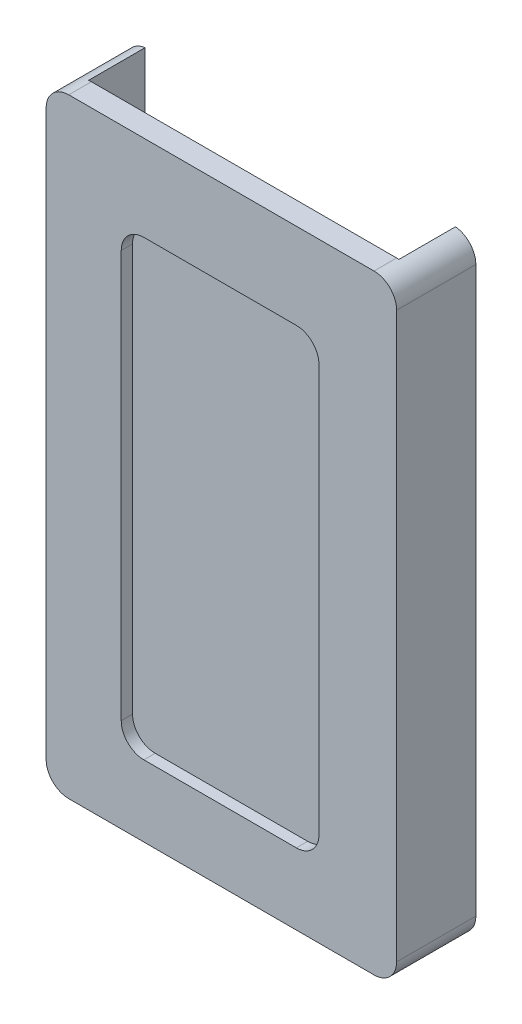
SolidWorks part; units mm, degrees
ref_plane "Front Plane" through (0, 0, 0) normal (0, 0, 1) x (1, 0, 0)
ref_plane "Top Plane" through (0, 0, 0) normal (0, 1, 0) x (1, 0, 0)
ref_plane "Right Plane" through (0, 0, 0) normal (1, 0, 0) x (0, 0, -1)
sketch "草图5" plane through (0, 0, 17) normal (0, 0, 1) x (1, 0, 0)
  line L0 (67.6414, -26.8877) -> (67.6414, -76.7564) construction
  line L1 (36.6667, -24.8877) -> (67.6414, -24.8877)
  line L2 (36.6667, -24.8877) -> (36.6667, -78.7564)
  line L3 (36.6667, -78.7564) -> (67.6414, -78.7564)
  line L4 (67.6414, -24.8877) -> (67.6414, -78.7564)
  line L5 (38.4139, -24.9037) -> (38.4139, -28.6161) construction
  line L6 (38.4139, -26.7599) -> (65.7955, -26.7599)
  line L7 (38.4139, -26.7599) -> (38.4139, -77.1753)
  line L8 (38.4139, -77.1753) -> (65.7955, -77.1753)
  line L9 (65.7955, -26.7599) -> (65.7955, -77.1753)
  point P14 (0, 0)
extrude "凸台-拉伸3" add sketch "草图5" along normal blind 5 contours L2 L1 L4 L3 | L7 L6 L9 L8
sketch "草图6" plane through (0, -24.8877, 0) normal (0, 1, 0) x (1, 0, 0)
  line L1 (38.4139, -17) -> (65.8413, -17)
  line L2 (38.4139, -17) -> (38.4139, -22)
  line L3 (38.4139, -22) -> (65.8413, -22)
  line L4 (65.8413, -17) -> (65.8413, -22)
  point P4 (0, 0)
extrude "切除-拉伸4" cut sketch "草图6" against normal blind 4
sketch "草图8" plane through (0, 0, 17) normal (0, 0, -1) x (-1, 0, 0)
  line L0 (-38.4139, -77.1753) -> (-65.7955, -77.1753) construction
  line L1 (-55.1901, -77.1753) -> (-49.0701, -77.1753)
  line L2 (-55.1901, -77.1753) -> (-55.1901, -78.7564)
  line L3 (-55.1901, -78.7564) -> (-49.0701, -78.7564)
  line L4 (-49.0701, -77.1753) -> (-49.0701, -78.7564)
  line L5 (-36.6667, -78.7564) -> (-67.6414, -78.7564) construction
extrude "切除-拉伸6" cut sketch "草图8" against normal blind 3 contours L2 L1 L4 L3
sketch "草图9" plane through (0, 0, 22) normal (0, 0, 1) x (1, 0, 0)
  line L1 (36.6667, -24.8877) -> (67.6414, -24.8877)
  line L2 (36.6667, -24.8877) -> (36.6667, -78.7564)
  line L3 (36.6667, -78.7564) -> (67.6414, -78.7564)
  line L4 (67.6414, -24.8877) -> (67.6414, -78.7564)
extrude "凸台-拉伸5" add sketch "草图9" along normal blind 2
sketch "草图10" plane through (0, 0, 24) normal (0, 0, 1) x (1, 0, 0)
  line L1 (43.3021, -32.4774) -> (60.7771, -32.4774)
  line L2 (43.3021, -32.4774) -> (43.3021, -72.4639)
  line L3 (43.3021, -72.4639) -> (60.7771, -72.4639)
  line L4 (60.7771, -32.4774) -> (60.7771, -72.4639)
extrude "切除-拉伸7" cut sketch "草图10" against normal blind 1
fillet "圆角1" radius 2 4 edges at (67.6414, -78.7564, 20.5) (36.6667, -78.7564, 20.5) (36.6667, -24.8877, 20.5) (67.6414, -24.8877, 20.5)
fillet "圆角2" radius 2 4 edges at (43.3021, -72.4639, 23.5) (60.7771, -72.4639, 23.5) (60.7771, -32.4774, 23.5) (43.3021, -32.4774, 23.5)
